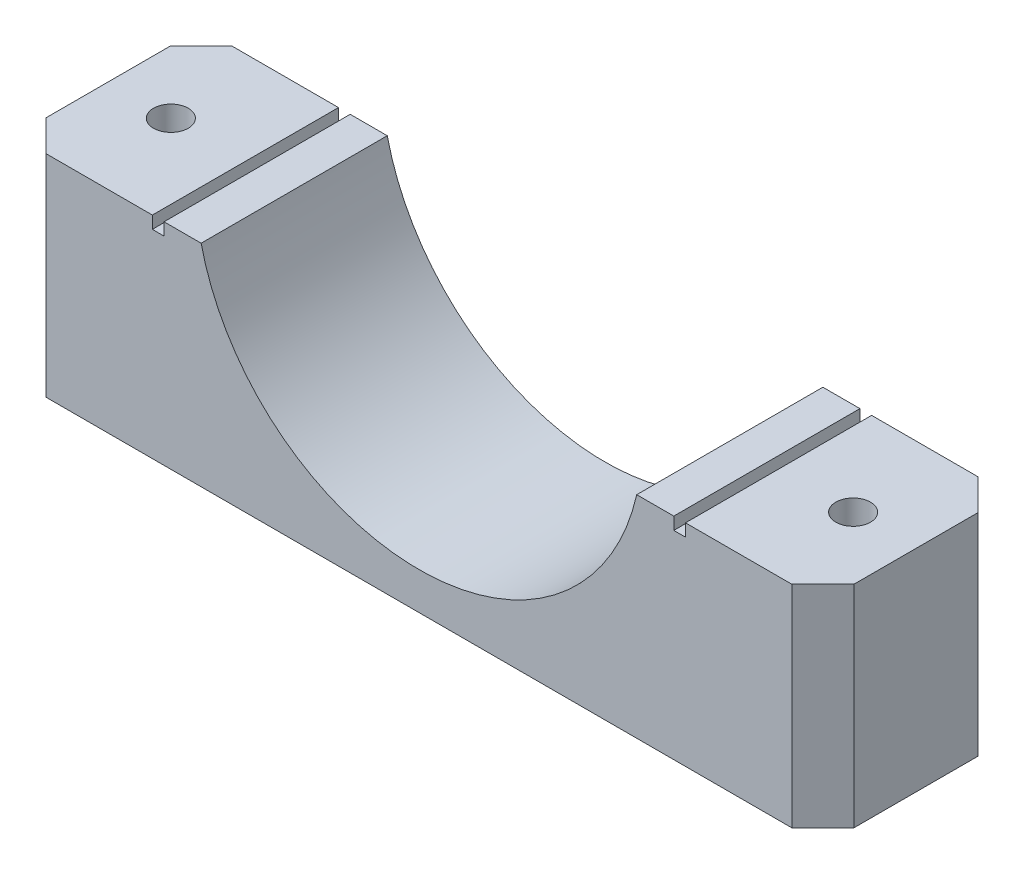
SolidWorks part; units mm, degrees
ref_plane "Front Plane" through (0, 0, 0) normal (0, 0, 1) x (1, 0, 0)
ref_plane "Top Plane" through (0, 0, 0) normal (0, 1, 0) x (1, 0, 0)
ref_plane "Right Plane" through (0, 0, 0) normal (1, 0, 0) x (0, 0, -1)
sketch "Sketch1" plane through (0, 0, 0) normal (0, 0, 1) x (1, 0, 0)
  line L0 (-17.5499, -4) -> (-32.5499, -4)
  line L1 (-32.5499, -4) -> (-32.5499, -21)
  line L2 (-32.5499, -21) -> (32.5499, -21)
  line L3 (32.5499, -21) -> (32.5499, -4)
  line L4 (32.5499, -4) -> (17.5499, -4)
  arc A0 (-17.5499, -4) -> (17.5499, -4) centre (0, 0) ccw
  dimension "D1" = 18
  dimension "D2" = 15
  dimension "D3" = 15
  dimension "D4" = 21
  dimension "D5" = 4
extrude "Boss-Extrude1" add sketch "Sketch1" along normal blind 15 contours L4 A0 L0 L1 L2 L3
chamfer "Chamfer1" distance 2.5 4 edges at (32.5499, -12.5, 0) (32.5499, -12.5, 15) (-32.5499, -12.5, 0) (-32.5499, -12.5, 15)
sketch "Sketch2" plane through (0, -4, 0) normal (0, 1, 0) x (1, 0, 0)
  line L0 (0, -55) -> (0, 55) construction
  circle A0 centre (27.4886, -7.5) radius 1.4
  circle A1 centre (-27.4886, -7.5) radius 1.4
  dimension "D1" = 2.8
extrude "Cut-Extrude1" cut sketch "Sketch2" against normal through all
sketch "Sketch3" plane through (0, -4, 0) normal (0, 1, 0) x (1, 0, 0)
  line L0 (-17.5499, 0) -> (-30.0499, 0) construction
  line L1 (-21.4797, 0) -> (-20.5371, 0)
  line L2 (-21.4797, 0) -> (-21.4797, -15)
  line L3 (-21.4797, -15) -> (-20.5371, -15)
  line L4 (-20.5371, 0) -> (-20.5371, -15)
  line L5 (-17.5499, -15) -> (-30.0499, -15) construction
extrude "Cut-Extrude2" cut sketch "Sketch3" against normal blind 1 contours L2 L1 L4 L3
mirror "Mirror1" about plane through (0, 0, 0) normal (1, 0, 0) of "Cut-Extrude2"
